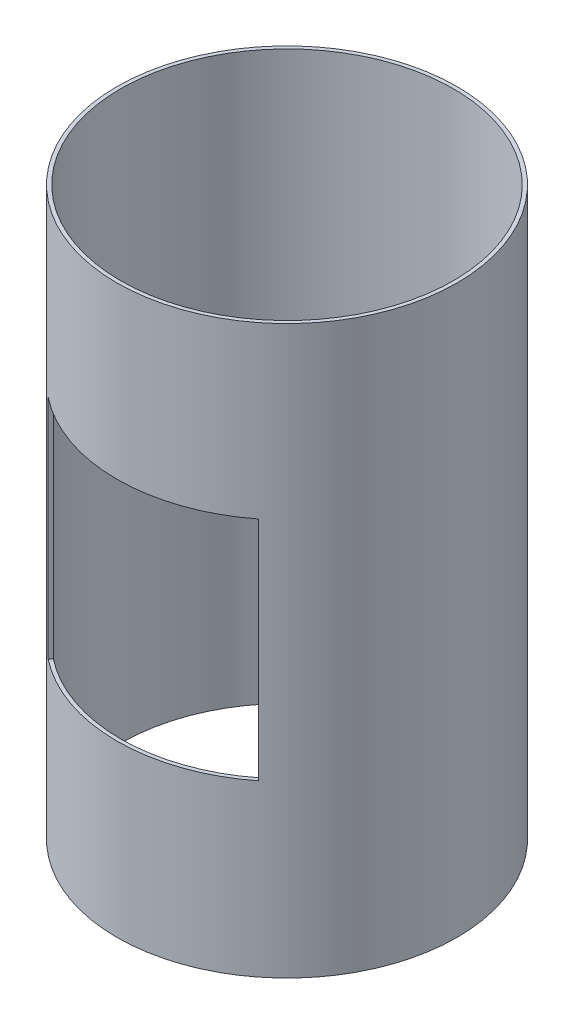
SolidWorks part; units mm, degrees
ref_plane "Front Plane" through (0, 0, 0) normal (0, 0, 1) x (1, 0, 0)
ref_plane "Top Plane" through (0, 0, 0) normal (0, 1, 0) x (1, 0, 0)
ref_plane "Right Plane" through (0, 0, 0) normal (1, 0, 0) x (0, 0, -1)
sketch "Sketch1" plane through (0, 0, 0) normal (0, 1, 0) x (1, 0, 0)
  circle A0 centre (0, 0) radius 76.2
  circle A1 centre (0, 0) radius 74.549
  dimension "D1" = 152.4
  dimension "D2" = 149.098
extrude "Boss-Extrude1" add sketch "Sketch1" along normal blind 254
sketch "Sketch2" plane through (0, 0, 0) normal (0, 0, 1) x (1, 0, 0)
  line L0 (-76.2, 254) -> (-76.2, 0) construction
  line L1 (-50.8, 177.8) -> (50.8, 177.8)
  line L2 (-50.8, 177.8) -> (-50.8, 76.2)
  line L3 (-50.8, 76.2) -> (50.8, 76.2)
  line L4 (50.8, 177.8) -> (50.8, 76.2)
  line L5 (76.2, 0) -> (76.2, 254) construction
  line L6 (-76.2, 0) -> (76.2, 0) construction
  dimension "D1" = 25.4
  dimension "D2" = 25.4
  dimension "D3" = 101.6
  dimension "D4" = 76.2
wrap "Wrap2" sketch "Sketch2" wrap type deboss source sketch "Sketch2" thickness 3.302 face at (0, 254, 76.2) parameters "D1"=3.302
